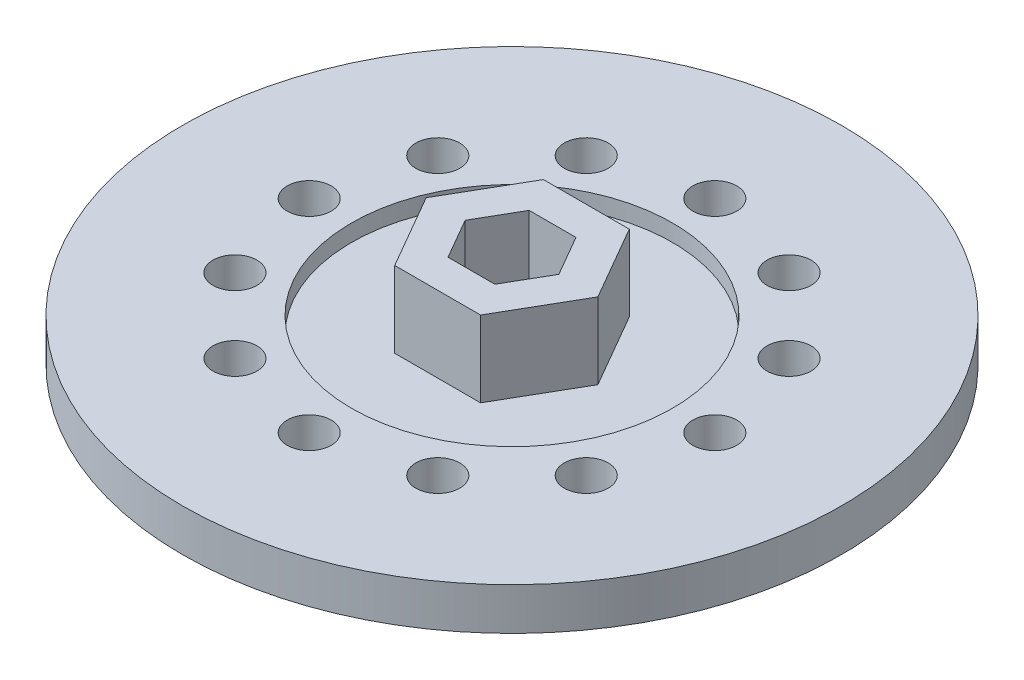
SolidWorks part; units mm, degrees
ref_plane "Front Plane" through (0, 0, 0) normal (0, 0, 1) x (1, 0, 0)
ref_plane "Top Plane" through (0, 0, 0) normal (0, 1, 0) x (1, 0, 0)
ref_plane "Right Plane" through (0, 0, 0) normal (1, 0, 0) x (0, 0, -1)
sketch "Sketch1" plane through (0, 0, 0) normal (0, 1, 0) x (1, 0, 0)
  circle A0 centre (0, 0) radius 49.53
  dimension "D1" = 99.06
extrude "Boss-Extrude1" add sketch "Sketch1" along normal blind 15.24
sketch "Sketch4" plane through (0, 15.24, 0) normal (0, 1, 0) x (1, 0, 0)
  line L0 (-3.5195, 6.096) -> (3.5195, 6.096)
  line L1 (3.5195, 6.096) -> (7.0391, 0)
  line L2 (7.0391, 0) -> (3.5195, -6.096)
  line L3 (3.5195, -6.096) -> (-3.5195, -6.096)
  line L4 (-3.5195, -6.096) -> (-7.0391, 0)
  line L5 (-7.0391, 0) -> (-3.5195, 6.096)
  point P7 (0, 6.096)
  dimension "D1" = 120
  dimension "D2" = 12.192
extrude "Hex hole" cut sketch "Sketch4" against normal blind 13.97 contours L5 L0 L1 L2 L3 L4
sketch "Sketch5" plane through (0, 1.27, 0) normal (0, 1, 0) x (1, 0, 0)
  circle A0 centre (0, 0) radius 4.191
  dimension "D1" = 8.382
extrude "Centerhole" cut sketch "Sketch5" against normal through all contours A0
sketch "Sketch6" plane through (0, 15.24, 0) normal (0, 1, 0) x (1, 0, 0)
  line L27 (12.9049, 0) -> (6.4525, 11.176)
  line L28 (6.4525, -11.176) -> (12.9049, 0)
  line L29 (-6.4525, -11.176) -> (6.4525, -11.176)
  line L30 (-12.9049, 0) -> (-6.4525, -11.176)
  line L31 (-6.4525, 11.176) -> (-12.9049, 0)
  line L32 (6.4525, 11.176) -> (-6.4525, 11.176)
  line L33 (12.9049, 0) -> (6.4525, 11.176)
  line L34 (6.4525, -11.176) -> (12.9049, 0)
  line L35 (-6.4525, -11.176) -> (6.4525, -11.176)
  line L36 (-12.9049, 0) -> (-6.4525, -11.176)
  line L37 (-6.4525, 11.176) -> (-12.9049, 0)
  line L38 (6.4525, 11.176) -> (-6.4525, 11.176)
  circle A2 centre (0, 0) radius 39.37
  circle A3 centre (0, 0) radius 39.37
  dimension "D1" = 10.16
  dimension "D2" = 5.08
extrude "Cut-Extrude1" cut sketch "Sketch6" against normal offset from surface (11.43 mm away) 3.81 up to face at (0, 0, 4.191)
sketch "Sketch7" plane through (0, 0, 0) normal (0, -1, 0) x (1, 0, 0)
  circle A0 centre (0, 30.48) radius 3.302
  circle A1 centre (15.24, 26.3965) radius 3.302
  circle A2 centre (26.3965, 15.24) radius 3.302
  circle A3 centre (30.48, 0) radius 3.302
  circle A4 centre (26.3965, -15.24) radius 3.302
  circle A5 centre (15.24, -26.3965) radius 3.302
  circle A6 centre (0, -30.48) radius 3.302
  circle A7 centre (-15.24, -26.3965) radius 3.302
  circle A8 centre (-26.3965, -15.24) radius 3.302
  circle A9 centre (-30.48, 0) radius 3.302
  circle A10 centre (-26.3965, 15.24) radius 3.302
  circle A11 centre (-15.24, 26.3965) radius 3.302
  point P27 (0, 0)
  dimension "D1" = 6.604
  dimension "D2" = 30.48
extrude "Cut-Extrude2" cut sketch "Sketch7" against normal through all
sketch "Sketch8" plane through (0, 15.24, 0) normal (0, 1, 0) x (1, 0, 0)
  circle A0 centre (0, 0) radius 39.37
  circle A1 centre (0, 0) radius 49.53
extrude "Cut-Extrude3" cut sketch "Sketch8" against normal up to surface (11.43 mm away) up to face at (-26.3965, 3.81, -11.938)
sketch "Sketch9" plane through (0, 3.81, 0) normal (0, 1, 0) x (1, 0, 0)
  circle A0 centre (0, 0) radius 24.13
  circle A1 centre (0, 0) radius 49.53
  circle A2 centre (0, 0) radius 49.53 construction
  circle A3 centre (0, 30.48) radius 3.302
  circle A4 centre (0, 30.48) radius 3.302 construction
  circle A5 centre (15.24, 26.3965) radius 3.302
  circle A6 centre (26.3965, 15.24) radius 3.302
  circle A7 centre (30.48, 0) radius 3.302
  circle A8 centre (26.3965, -15.24) radius 3.302
  circle A9 centre (15.24, -26.3965) radius 3.302
  circle A10 centre (0, -30.48) radius 3.302
  circle A11 centre (-15.24, -26.3965) radius 3.302
  circle A12 centre (-26.3965, -15.24) radius 3.302
  circle A13 centre (-30.48, 0) radius 3.302
  circle A14 centre (-26.3965, 15.24) radius 3.302
  circle A15 centre (-15.24, 26.3965) radius 3.302
  point P36 (0, 0)
  dimension "D1" = 25.4
  dimension "D2" = 12
extrude "Boss-Extrude2" add sketch "Sketch9" along normal blind 2.54
